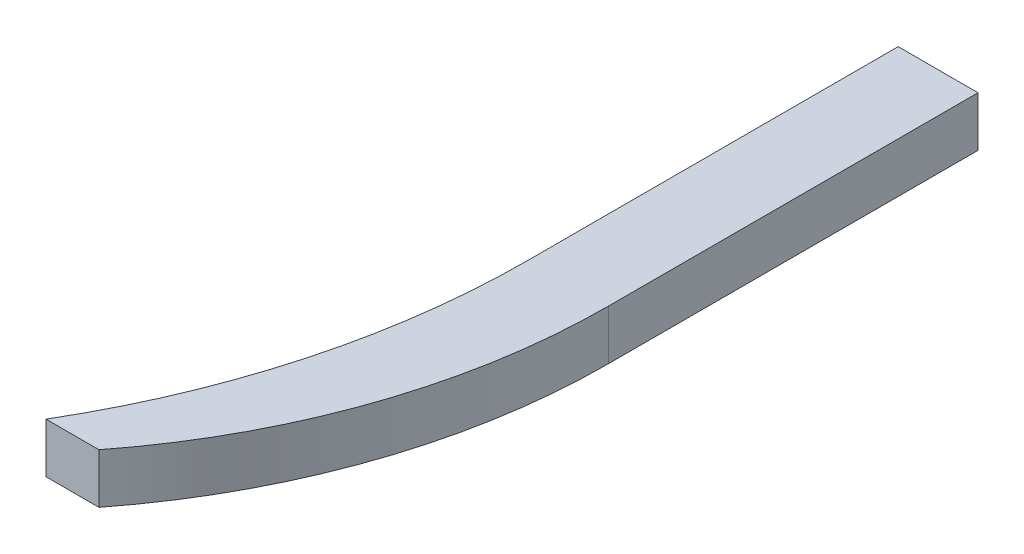
SolidWorks part; units mm, degrees
ref_plane "Front Plane" through (0, 0, 0) normal (0, 0, 1) x (1, 0, 0)
ref_plane "Top Plane" through (0, 0, 0) normal (0, 1, 0) x (1, 0, 0)
ref_plane "Right Plane" through (0, 0, 0) normal (1, 0, 0) x (0, 0, -1)
sketch "Sketch1" plane through (0, 0, 0) normal (0, 1, 0) x (1, 0, 0)
  line L0 (0, 0) -> (8, 0)
  line L1 (8, 0) -> (8, -45.7526) construction
  line L2 (8, 0) -> (8, -37)
  line L3 (0, -8) -> (0, 0)
  line L4 (0, -8) -> (0, -37)
  line L5 (0, -8) -> (0, -8) construction
  arc A2 (8, -37) -> (-22, -90) centre (-53.8167, -37) cw
  arc A3 (0, -37) -> (-22, -90) centre (-74.8409, -37) cw
  arc A4 (0, -37) -> (-26.1176, -83.141) centre (-53.8167, -37) cw construction
  dimension "D1" = 8
  dimension "D2" = 90
  dimension "D3" = 30
  dimension "D5" = 37
  dimension "D4" = 8
extrude "Boss-Extrude1" add sketch "Sketch1" along normal blind 5
sketch "Sketch2" plane through (0, 5, 0) normal (0, 1, 0) x (1, 0, 0)
  line L0 (-10.3649, -75) -> (-5.0591, -75)
  line L4 (0, 0) -> (0, -37)
  line L5 (8, -37) -> (8, 0)
  line L6 (8, 0) -> (0, 0)
  arc A1 (-22, -90) -> (8, -37) centre (-53.8167, -37) ccw construction
  arc A2 (-22, -90) -> (0, -37) centre (-74.8409, -37) ccw construction
  arc A4 (-22, -90) -> (0, -37) centre (-74.8409, -37) ccw
  arc A5 (-22, -90) -> (8, -37) centre (-53.8167, -37) ccw
  arc A6 (-22, -90) -> (-10.3649, -75) centre (-74.8409, -37) ccw
  arc A7 (-22, -90) -> (-5.0591, -75) centre (-53.8167, -37) ccw
  point P2 (-8.0085, -70.6836)
  dimension "D2" = 15
  dimension "D1" = 0
extrude "Cut-Extrude1" cut sketch "Sketch2" against normal blind 10
